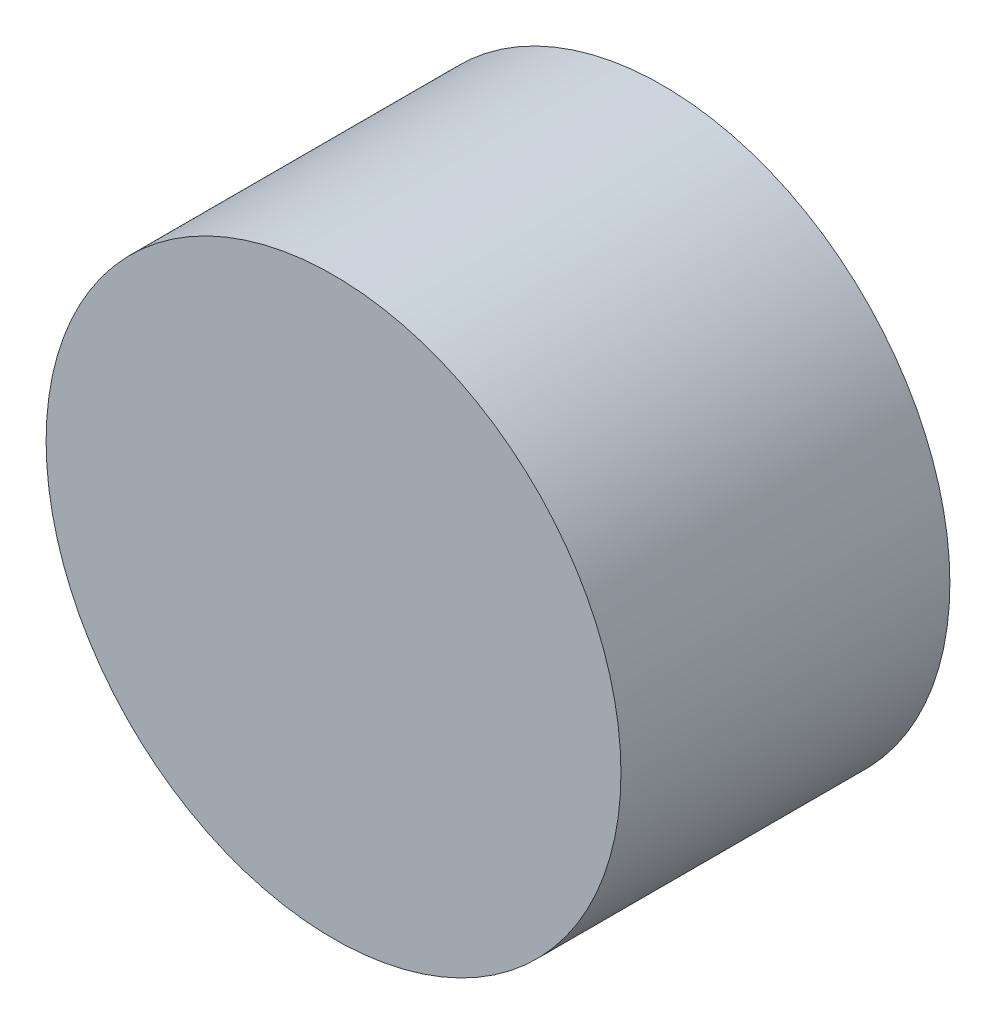
SolidWorks part; units mm, degrees
ref_plane "Front Plane" through (0, 0, 0) normal (0, 0, 1) x (1, 0, 0)
ref_plane "Top Plane" through (0, 0, 0) normal (0, 1, 0) x (1, 0, 0)
ref_plane "Right Plane" through (0, 0, 0) normal (1, 0, 0) x (0, 0, -1)
sketch "Sketch1" plane through (0, 0, 0) normal (0, 0, 1) x (1, 0, 0)
  circle A0 centre (0, 0) radius 26.65
  dimension "D1" = 53.3
extrude "Boss-Extrude2" add sketch "Sketch1" along normal blind 30.5
